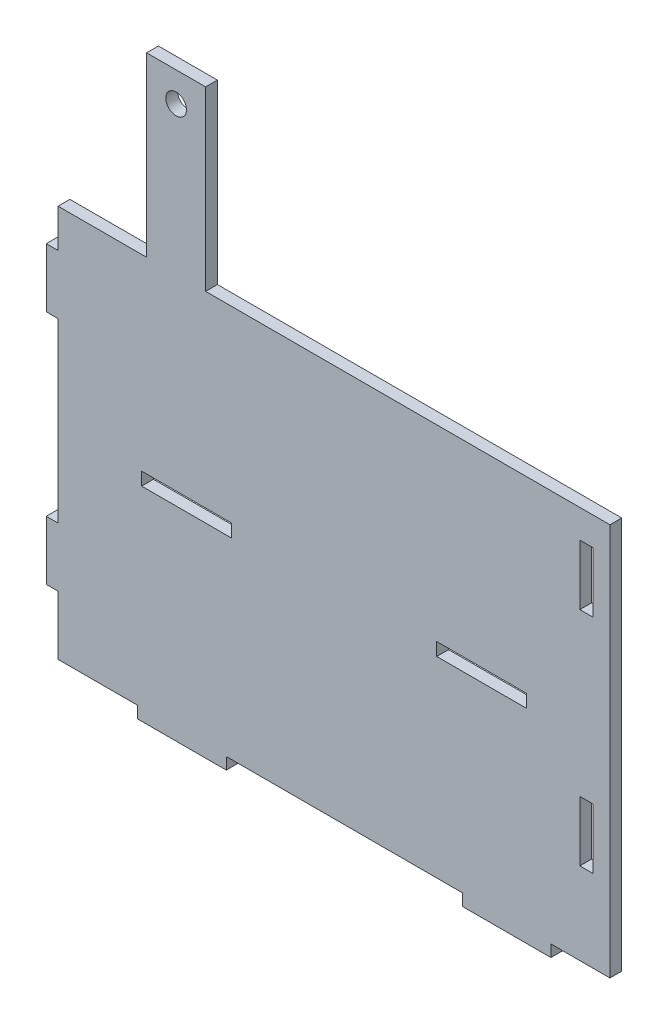
SolidWorks part; units mm, degrees
ref_plane "Спереди" through (0, 0, 0) normal (0, 0, 1) x (1, 0, 0)
ref_plane "Сверху" through (0, 0, 0) normal (0, 1, 0) x (1, 0, 0)
ref_plane "Справа" through (0, 0, 0) normal (1, 0, 0) x (0, 0, -1)
sketch "Эскиз1" plane through (0, 0, 0) normal (0, 0, 1) x (1, 0, 0)
  line L0 (0, 0) -> (0, 133)
  line L1 (0, 0) -> (187, 0)
  line L2 (187, 0) -> (187, 133)
  line L3 (187, 133) -> (0, 133)
  line L4 (93.5, 0) -> (93.5, 65) construction
  line L5 (176.8, 48.2) -> (181.2, 48.2)
  line L6 (176.8, 48.2) -> (176.8, 27.8)
  line L7 (176.8, 27.8) -> (181.2, 27.8)
  line L8 (181.2, 48.2) -> (181.2, 27.8)
  line L13 (187, 66.5) -> (172.8782, 66.5) construction
  line L14 (0, 66.5) -> (18.3539, 66.5) construction
  line L15 (0, 20) -> (-4, 20)
  line L16 (136.9954, 0) -> (166.9954, 0)
  line L17 (136.9954, 0) -> (136.9954, -4)
  line L18 (136.9954, -4) -> (166.9954, -4)
  line L19 (166.9954, 0) -> (166.9954, -4)
  line L20 (-4, 40) -> (-4, 20)
  line L21 (0, 40) -> (-4, 40)
  line L22 (0, 40) -> (0, 20)
  line L23 (56.9954, -4) -> (26.9954, -4)
  line L24 (26.9954, 0) -> (26.9954, -4)
  line L25 (56.9954, 0) -> (26.9954, 0)
  line L26 (56.9954, 0) -> (56.9954, -4)
  line L31 (-4, 100) -> (-4, 40) construction
  line L32 (-4, 100) -> (0, 100)
  line L33 (-4, 100) -> (-4, 120)
  line L34 (-4, 120) -> (0, 120)
  line L35 (0, 100) -> (0, 120)
  line L36 (41.9954, 0) -> (41.9954, -4) construction
  line L37 (151.9954, 0) -> (151.9954, -4) construction
  line L38 (-4, 30) -> (0, 30) construction
  line L39 (-4, 110) -> (0, 110) construction
  line L40 (93.5, 65) -> (58.7, 65) construction
  line L41 (58.7, 65) -> (28.3, 65)
  line L42 (58.7, 65) -> (58.7, 69.4)
  line L43 (58.7, 69.4) -> (28.3, 69.4)
  line L44 (28.3, 65) -> (28.3, 69.4)
  line L45 (128.3, 65) -> (158.7, 65)
  line L46 (128.3, 65) -> (128.3, 69.4)
  line L47 (128.3, 69.4) -> (158.7, 69.4)
  line L48 (158.7, 65) -> (158.7, 69.4)
  line L49 (93.5, 65) -> (128.3, 65) construction
  line L50 (43.5, 69.4) -> (43.5, 65) construction
  line L51 (143.5, 69.4) -> (143.5, 65) construction
  line L52 (179, 123.4) -> (179, 131.3455) construction
  line L53 (181.2, 103) -> (176.8, 103)
  line L54 (181.2, 103) -> (181.2, 123.4)
  line L55 (181.2, 123.4) -> (176.8, 123.4)
  line L56 (176.8, 103) -> (176.8, 123.4)
  line L57 (179, 48.2) -> (179, 27.8) construction
  line L58 (176.8, 38) -> (181.2, 38) construction
  line L59 (40, 193) -> (40, 183) construction
  line L60 (30, 133) -> (50, 133)
  line L61 (30, 133) -> (30, 193)
  line L62 (30, 193) -> (50, 193)
  line L63 (50, 133) -> (50, 193)
  circle A0 centre (40, 183) radius 3.5
  point P47 (143.5, 69.4)
  point P69 (53.4966, -4.2619)
  point P70 (23.5771, -4)
  point P71 (53.5, 0)
  point P72 (134.7465, 0)
  point P73 (0, 100)
  point P76 (176.8, 45.8992)
  dimension "D32" = 7
  dimension "D1" = 133
  dimension "D2" = 133
  dimension "D3" = 187
  dimension "D4" = 4.4
  dimension "D5" = 20.4
  dimension "D6" = 38
  dimension "D7" = 8
  dimension "D8" = 110
  dimension "D9" = 30
  dimension "D10" = 30
  dimension "D11" = 4
  dimension "D13" = 20
  dimension "D14" = 80
  dimension "D15" = 4
  dimension "D16" = 20
  dimension "D17" = 20
  dimension "D18" = 30.4
  dimension "D19" = 30.4
  dimension "D20" = 4.4
  dimension "D21" = 4.4
  dimension "D22" = 50
  dimension "D23" = 100
  dimension "D24" = 65
  dimension "D25" = 20.4
  dimension "D26" = 103
  dimension "D27" = 4.4
  dimension "D28" = 8
  dimension "D29" = 20
  dimension "D30" = 30
  dimension "D31" = 60
  dimension "D33" = 10
  dimension "D34" = 4
  dimension "D35" = 41.9954
extrude "Бобышка-Вытянуть1" add sketch "Эскиз1" along normal blind 4 contours L2 L3 L0 L1 L48 L45 L46 L47 L5 L8 L7 L6 L41 L44 L43 L42 | L3 L63 L62 L61 A0 | L17 L16 L19 L18 | L23 L24 L25 L26 | L15 L20 L21 L22 | L33 L32 L35 L34
